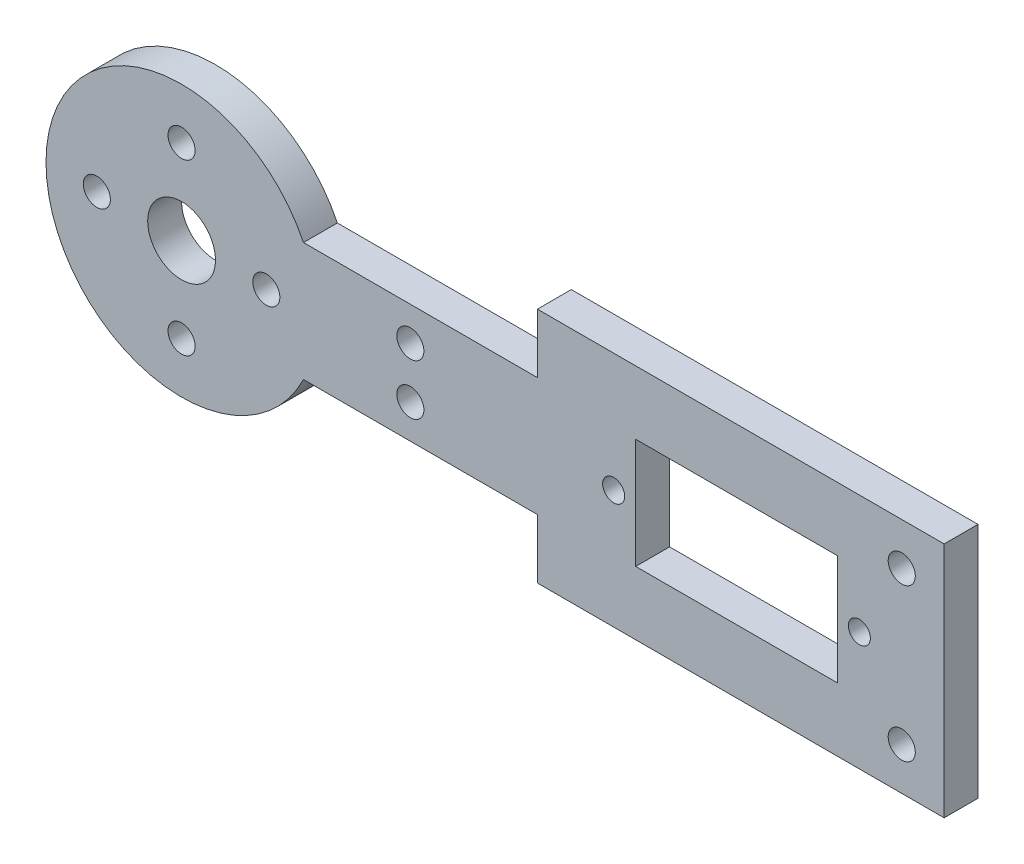
SolidWorks part; units mm, degrees
ref_plane "Front Plane" through (0, 0, 0) normal (0, 0, 1) x (1, 0, 0)
ref_plane "Top Plane" through (0, 0, 0) normal (0, 1, 0) x (1, 0, 0)
ref_plane "Right Plane" through (0, 0, 0) normal (1, 0, 0) x (0, 0, -1)
sketch "Main_web_profile" plane through (0, 0, 0) normal (0, 0, 1) x (1, 0, 0)
  line L1 (0, -7) -> (60, -7)
  line L2 (0, -7) -> (0, 7)
  line L3 (0, 7) -> (60, 7)
  line L4 (60, -7) -> (60, 7)
  dimension "D1" = 60
  dimension "D2" = 14
extrude "Main_web" add sketch "Main_web_profile" along normal blind 4
sketch "Shoulder_horn_flange_profile" plane through (0, 0, 0) normal (0, 0, 1) x (1, 0, 0)
  circle A0 centre (0, 0) radius 16
  dimension "D1" = 32
extrude "Shoulder_horn_flange" add sketch "Shoulder_horn_flange_profile" along normal blind 4
sketch "Elbow_servo_mount_profile" plane through (0, 0, 0) normal (0, 0, 1) x (1, 0, 0)
  line L1 (42, -14) -> (90, -14)
  line L2 (42, -14) -> (42, 14)
  line L3 (42, 14) -> (90, 14)
  line L4 (90, -14) -> (90, 14)
  dimension "D1" = 48
  dimension "D2" = 28
extrude "Elbow_servo_mount" add sketch "Elbow_servo_mount_profile" along normal blind 4
sketch "SG90_body_clearance_profile" plane through (0, 0, 0) normal (0, 0, 1) x (1, 0, 0)
  line L1 (53.6, -6.5) -> (77.4, -6.5)
  line L2 (53.6, -6.5) -> (53.6, 6.5)
  line L3 (53.6, 6.5) -> (77.4, 6.5)
  line L4 (77.4, -6.5) -> (77.4, 6.5)
  dimension "D1" = 23.8
  dimension "D2" = 13
extrude "SG90_body_clearance" cut sketch "SG90_body_clearance_profile" along normal through all from offset 5
sketch "Elbow_tab_fasteners_profile" plane through (0, 0, 0) normal (0, 0, 1) x (1, 0, 0)
  circle A0 centre (51, 0) radius 1.3
  circle A1 centre (80, 0) radius 1.3
  dimension "D1" = 2.6
  dimension "D2" = 2.6
extrude "Elbow_tab_fasteners" cut sketch "Elbow_tab_fasteners_profile" along normal through all from offset 50
sketch "Shoulder_center_screw_access_profile" plane through (0, 0, 0) normal (0, 0, 1) x (1, 0, 0)
  circle A0 centre (0, 0) radius 4
  dimension "D1" = 8
extrude "Shoulder_center_screw_access" cut sketch "Shoulder_center_screw_access_profile" along normal through all from offset 50
sketch "Shoulder_horn_bolt_pattern_profile" plane through (0, 0, 0) normal (0, 0, 1) x (1, 0, 0)
  circle A0 centre (0, 10) radius 1.6
  circle A1 centre (0, -10) radius 1.6
  circle A2 centre (10, 0) radius 1.6
  circle A3 centre (-10, 0) radius 1.6
  dimension "D1" = 3.2
  dimension "D2" = 3.2
  dimension "D3" = 3.2
  dimension "D4" = 3.2
extrude "Shoulder_horn_bolt_pattern" cut sketch "Shoulder_horn_bolt_pattern_profile" along normal through all from offset 50
sketch "Cable_tie_holes_profile" plane through (0, 0, 0) normal (0, 0, 1) x (1, 0, 0)
  circle A0 centre (27, -3) radius 1.6
  circle A1 centre (27, 3) radius 1.6
  dimension "D1" = 3.2
  dimension "D2" = 3.2
extrude "Cable_tie_holes" cut sketch "Cable_tie_holes_profile" along normal through all from offset 50
sketch "Passive_cheek_standoffs_profile" plane through (0, 0, 0) normal (0, 0, 1) x (1, 0, 0)
  circle A0 centre (85, -9) radius 1.6
  circle A1 centre (85, 9) radius 1.6
  dimension "D1" = 3.2
  dimension "D2" = 3.2
extrude "Passive_cheek_standoffs" cut sketch "Passive_cheek_standoffs_profile" along normal through all from offset 50
